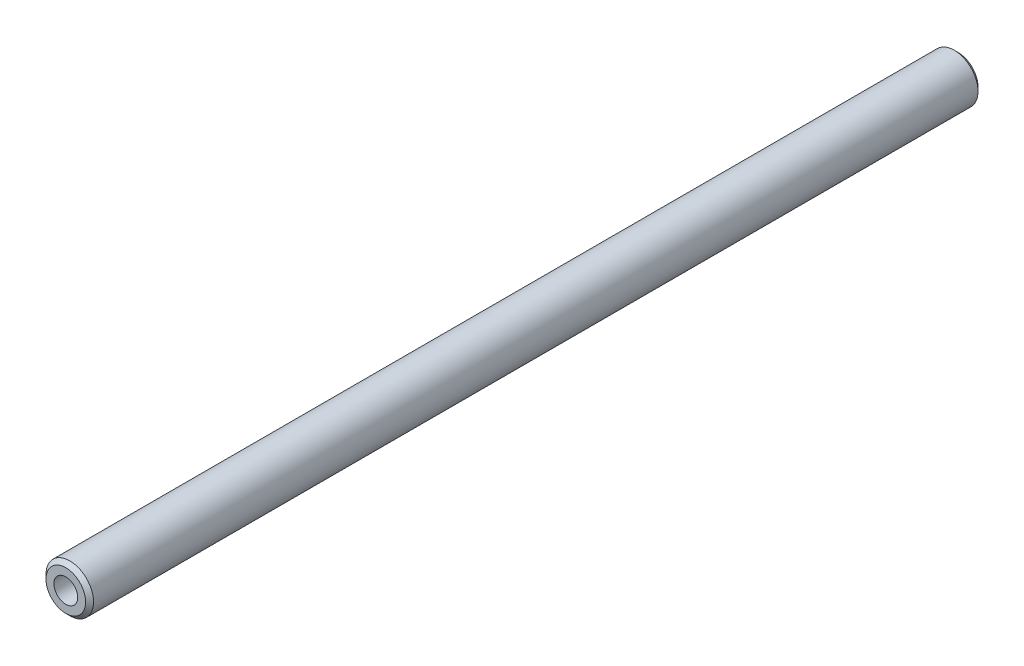
SolidWorks part; units mm, degrees
ref_plane "前视基准面" through (0, 0, 0) normal (0, 0, 1) x (1, 0, 0)
ref_plane "上视基准面" through (0, 0, 0) normal (0, 1, 0) x (1, 0, 0)
ref_plane "右视基准面" through (0, 0, 0) normal (1, 0, 0) x (0, 0, -1)
other "Configuration Table"
sketch "草图1" plane through (0, 0, 0) normal (0, 0, 1) x (1, 0, 0)
  circle A0 centre (0, 0) radius 3
  circle A1 centre (0, 0) radius 6
  dimension "D1" = 6
  dimension "D2" = 12
extrude "凸台-拉伸1" add sketch "草图1" along normal blind 225
chamfer "倒角1" distance 1 angle 45 2 edges at (6, 0, 225) (6, 0, 0)
